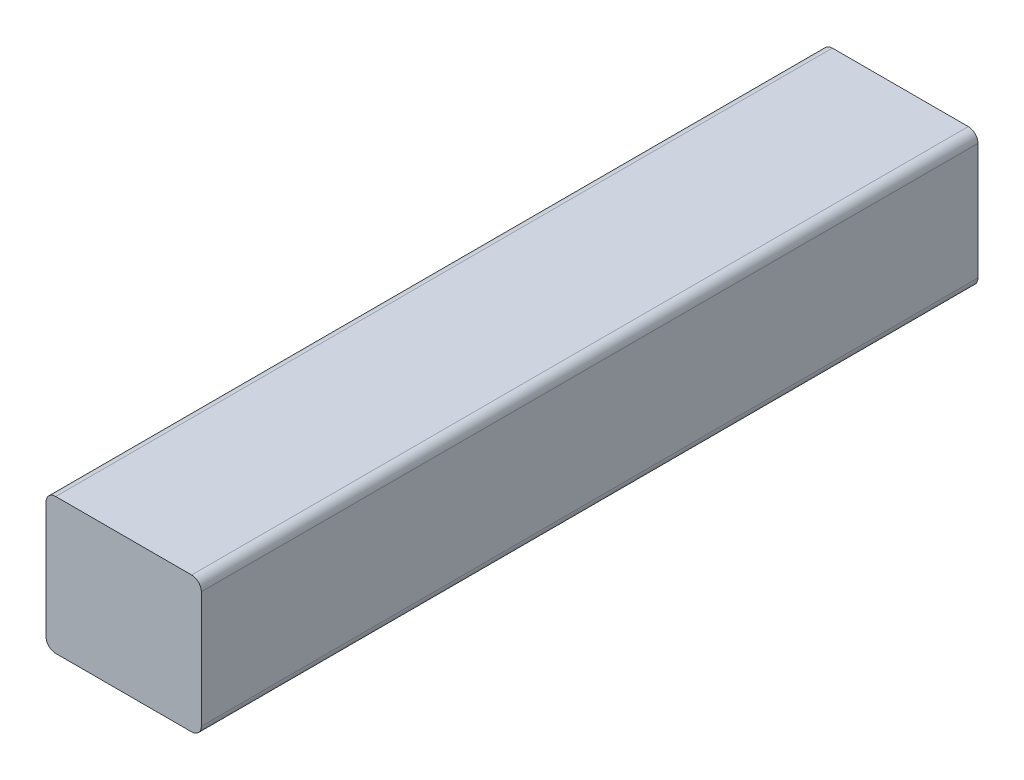
SolidWorks part; units mm, degrees
ref_plane "Front Plane" through (0, 0, 0) normal (0, 0, 1) x (1, 0, 0)
ref_plane "Top Plane" through (0, 0, 0) normal (0, 1, 0) x (1, 0, 0)
ref_plane "Right Plane" through (0, 0, 0) normal (1, 0, 0) x (0, 0, -1)
sketch "Sketch1" plane through (0, 0, 0) normal (0, 0, 1) x (1, 0, 0)
  line L1 (-4, 3.5) -> (4, 3.5)
  line L2 (-4, 3.5) -> (-4, -3.5)
  line L3 (-4, -3.5) -> (4, -3.5)
  line L4 (4, 3.5) -> (4, -3.5)
  line L5 (-4, 3.5) -> (4, -3.5) construction
  line L6 (-4, -3.5) -> (4, 3.5) construction
  point P0 (0, 0)
  dimension "D1" = 8
  dimension "D2" = 7
extrude "Boss-Extrude1" add sketch "Sketch1" along normal blind 40
fillet "Fillet1" radius 0.5 4 edges at (4, 3.5, 20) (-4, 3.5, 20) (-4, -3.5, 20) (4, -3.5, 20)
